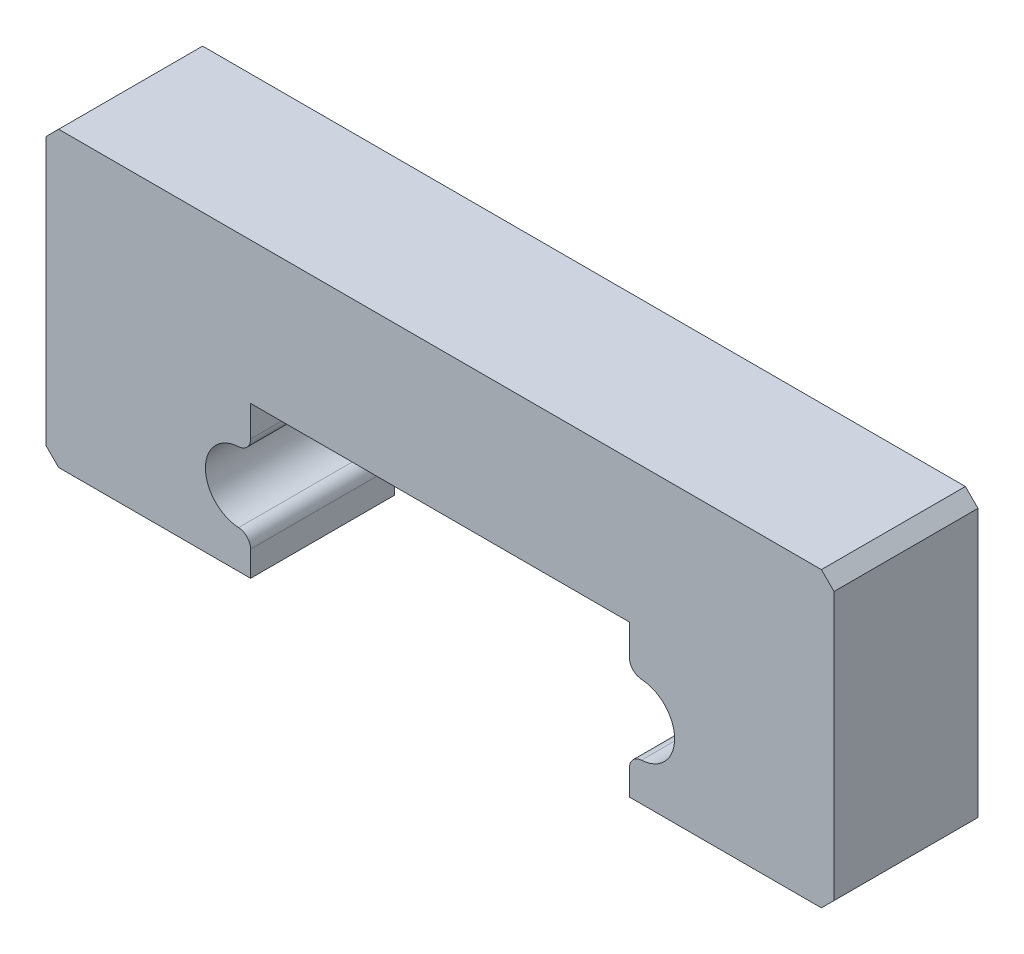
SolidWorks part; units mm, degrees
material "ABS"
ref_plane "Front Plane" through (0, 0, 0) normal (0, 0, 1) x (1, 0, 0)
ref_plane "Top Plane" through (0, 0, 0) normal (0, 1, 0) x (1, 0, 0)
ref_plane "Right Plane" through (0, 0, 0) normal (1, 0, 0) x (0, 0, -1)
sketch "Sketch1" plane through (0, 0, 0) normal (0, 0, 1) x (1, 0, 0)
  line L0 (0, 5.8) -> (0, -5.8) construction
  line L19 (-7.5, -5.8) -> (-15.1, -5.8)
  line L20 (-15.1, -5.8) -> (-15.6, -5.3)
  line L21 (-15.6, -5.3) -> (-15.6, 5.3)
  line L22 (-15.6, 5.3) -> (-15.1, 5.8)
  line L23 (-15.1, 5.8) -> (15.1, 5.8)
  line L24 (-7.5, -5.8) -> (-7.5, -4.2402)
  line L25 (-7.5, -1.5798) -> (-7.5, 0.2)
  line L26 (-7.5, 0.2) -> (7.5, 0.2)
  line L27 (7.5, -1.5798) -> (7.5, 0.2)
  line L28 (7.5, -5.8) -> (7.5, -4.2402)
  line L29 (7.5, -5.8) -> (15.1, -5.8)
  line L30 (15.1, -5.8) -> (15.6, -5.3)
  line L31 (15.6, -5.3) -> (15.6, 5.3)
  line L32 (15.6, 5.3) -> (15.1, 5.8)
  circle A4 centre (-7.9, -2.91) radius 1.389 construction
  circle A5 centre (-5.9, -2.91) radius 0.6 construction
  arc A6 (-7.5, -1.5798) -> (-7.5, -4.2402) centre (-7.9, -2.91) ccw
  arc A7 (7.5, -1.5798) -> (7.5, -4.2402) centre (7.9, -2.91) cw
  point P3 (0, 0)
  point P18 (0, 0.2)
  dimension "D8" = 2.778
  dimension "D9" = 7.9
  dimension "D10" = 2.89
  dimension "D11" = 1.2
  dimension "D12" = 5.9
  dimension "D13" = 2.89
  dimension "D1" = 11.6
  dimension "D2" = 0.5
  dimension "D3" = 0.5
  dimension "D4" = 0.5
  dimension "D5" = 0.5
  dimension "D6" = 15.6
  dimension "D7" = 7.5
  dimension "D14" = 6
extrude "Boss-Extrude1" add sketch "Sketch1" against normal blind 5.7 contours L27 A7 L28 L29 L30 L31 L32 L23 L22 L21 L20 L19 L24 A6 L25 L26
fillet "Fillet1" radius 0.5 4 edges at (7.5, -1.5798, -2.85) (7.5, -4.2402, -2.85) (-7.5, -1.5798, -2.85) (-7.5, -4.2402, -2.85)
